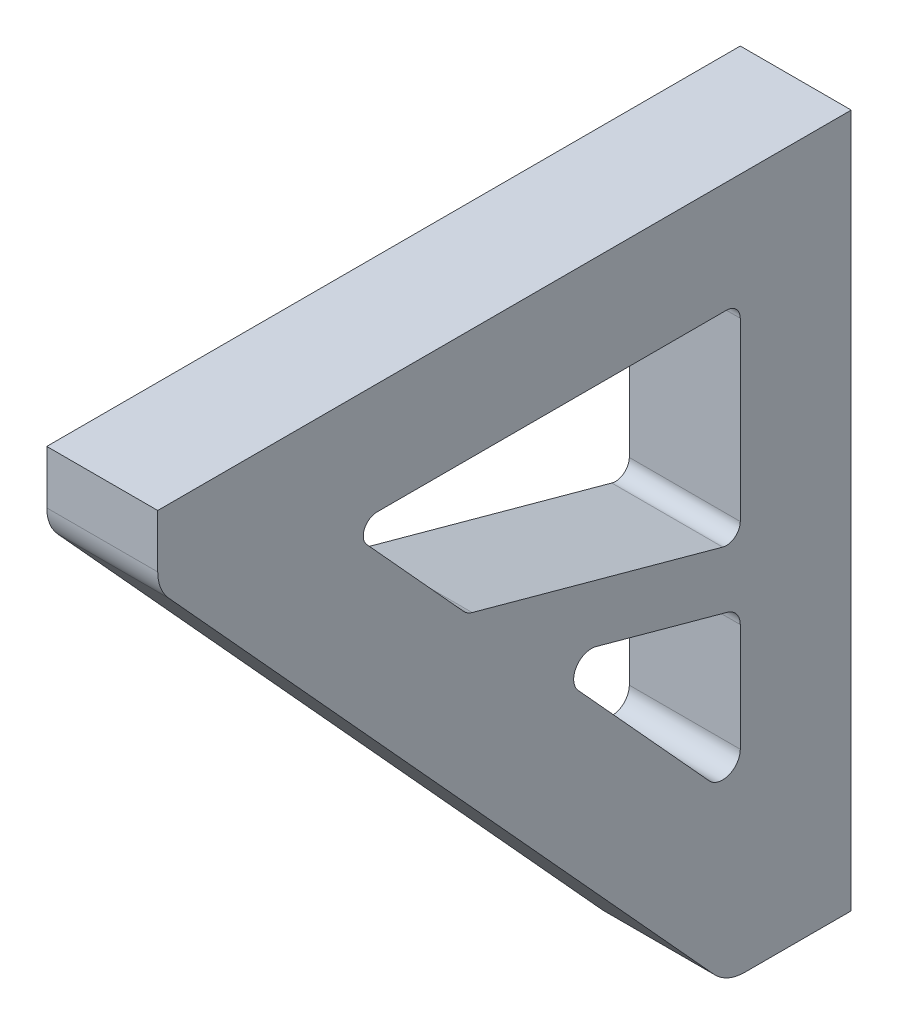
SolidWorks part; units mm, degrees
ref_plane "Front Plane" through (0, 0, 0) normal (0, 0, 1) x (1, 0, 0)
ref_plane "Top Plane" through (0, 0, 0) normal (0, 1, 0) x (1, 0, 0)
ref_plane "Right Plane" through (0, 0, 0) normal (1, 0, 0) x (0, 0, -1)
sketch "Sketch1" plane through (0, 0, 0) normal (0, 0, 1) x (1, 0, 0)
  line L0 (0, 0) -> (0, 50)
  line L1 (0, 50) -> (8, 50)
  line L2 (8, 50) -> (8, 0)
  line L3 (8, 0) -> (0, 0)
extrude "Boss-Extrude1" add sketch "Sketch1" along normal blind 50
sketch "Sketch2" plane through (0, 0, 0) normal (-1, 0, 0) x (0, 0, 1)
  line L0 (9, 0) -> (50, 45)
  line L1 (50, 0) -> (0, 0) construction
  line L2 (50, 50) -> (50, 0) construction
  line L3 (50, 50) -> (0, 50) construction
  line L4 (34.9194, 40.3265) -> (27.9392, 32.6653)
  line L5 (27.3301, 32.2923) -> (9.2641, 27.3461)
  line L6 (8, 28.3106) -> (8, 41)
  line L7 (9, 42) -> (34.1802, 42)
  line L8 (0, 50) -> (0, 0) construction
  line L9 (27.6887, 32.3904) -> (1.0292, 3.1299) construction
  line L10 (19.6779, 23.598) -> (10.2296, 13.228)
  line L11 (8, 14.0913) -> (8, 21.8746)
  line L12 (8.9434, 23.1111) -> (18.3917, 25.6979)
  line L13 (9, 0) -> (50, 0)
  line L14 (50, 0) -> (50, 45)
  arc A0 (34.9194, 40.3265) -> (34.1802, 42) centre (34.1802, 41) ccw
  arc A1 (9.2641, 27.3461) -> (8, 28.3106) centre (9, 28.3106) cw
  arc A2 (8, 41) -> (9, 42) centre (9, 41) cw
  arc A3 (10.2296, 13.228) -> (8, 14.0913) centre (9.282, 14.0913) cw
  arc A4 (19.6779, 23.598) -> (18.3917, 25.6979) centre (18.7302, 24.4614) ccw
  arc A5 (8.9434, 23.1111) -> (8, 21.8746) centre (9.282, 21.8746) ccw
  arc A6 (27.9392, 32.6653) -> (27.3301, 32.2923) centre (26.9916, 33.5287) cw
  point P23 (8, 27)
  point P26 (8, 42)
  point P29 (8, 10.7809)
  point P32 (22.6544, 26.8649)
  dimension "D7" = 1
  dimension "D9" = 1.282
  dimension "D1" = 5
  dimension "D2" = 9
  dimension "D3" = 8
  dimension "D4" = 8
  dimension "D5" = 8
  dimension "D6" = 15
  dimension "D8" = 4
extrude "Cut-Extrude1" cut sketch "Sketch2" against normal through all
fillet "Fillet1" radius 3 2 edges at (4, 0, 9) (4, 45, 50)
